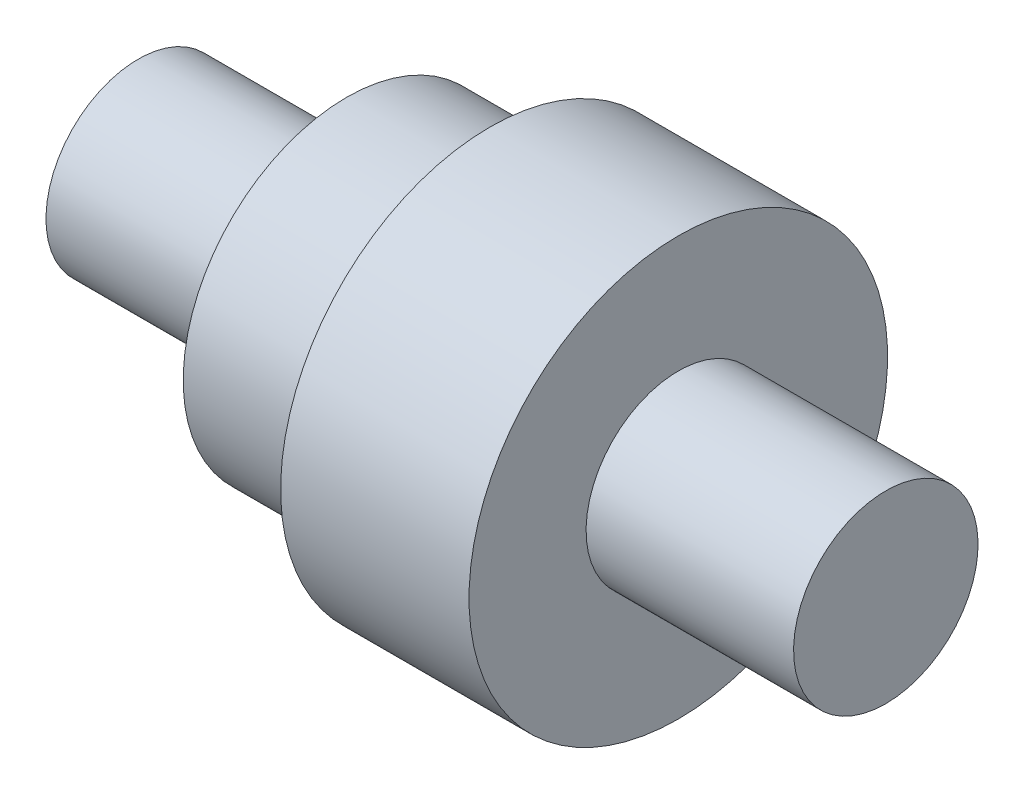
SolidWorks part; units mm, degrees
ref_plane "Front Plane" through (0, 0, 0) normal (0, 0, 1) x (1, 0, 0)
ref_plane "Top Plane" through (0, 0, 0) normal (0, 1, 0) x (1, 0, 0)
ref_plane "Right Plane" through (0, 0, 0) normal (1, 0, 0) x (0, 0, -1)
sketch "Sketch1" plane through (0, 0, 0) normal (0, 0, 1) x (1, 0, 0)
  line L0 (0, 7.11) -> (6.4, 7.11)
  line L1 (6.4, 7.11) -> (6.4, 0)
  line L2 (0, 7.11) -> (0, 5.55)
  line L3 (0, 5.55) -> (-4.87, 5.55)
  line L4 (-4.87, 5.55) -> (-4.87, 0)
  line L5 (-4.87, 0) -> (6.4, 0)
  line L6 (-11.95, 3.1336) -> (-11.95, 0)
  line L7 (-11.95, 3.1336) -> (13.45, 3.1336)
  line L8 (13.45, 0) -> (13.45, 3.1336)
  line L9 (-11.95, 0) -> (13.45, 0)
  dimension "D1" = 4.87
  dimension "D2" = 6.4
  dimension "D3" = 7.11
  dimension "D4" = 5.55
  dimension "D5" = 0
  dimension "D6" = 0
  dimension "D7" = 11.95
  dimension "D8" = 25.4
revolve "Revolve1" add sketch "Sketch1" angle 360 about L5
